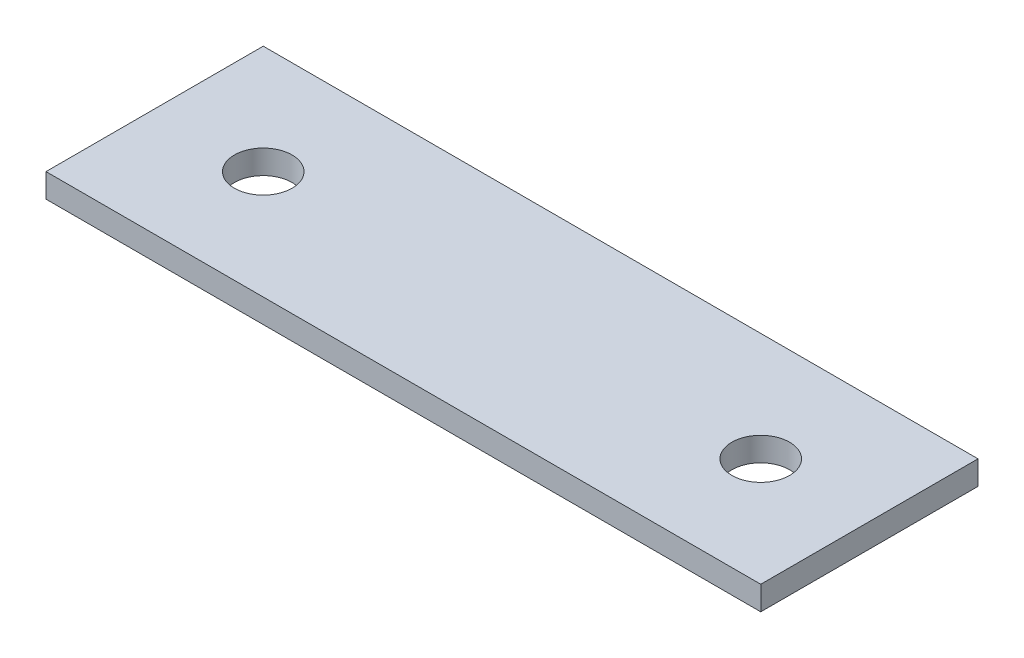
SolidWorks part; units mm, degrees
ref_plane "Front Plane" through (0, 0, 0) normal (0, 0, 1) x (1, 0, 0)
ref_plane "Top Plane" through (0, 0, 0) normal (0, 1, 0) x (1, 0, 0)
ref_plane "Right Plane" through (0, 0, 0) normal (1, 0, 0) x (0, 0, -1)
sketch "Sketch1" plane through (0, 0, 0) normal (0, 1, 0) x (1, 0, 0)
  line L0 (-41.783, 0) -> (41.783, 0) construction
  line L1 (-41.783, 12.7) -> (41.783, 12.7)
  line L2 (-41.783, 12.7) -> (-41.783, -12.7)
  line L3 (-41.783, -12.7) -> (41.783, -12.7)
  line L4 (41.783, 12.7) -> (41.783, -12.7)
  line L5 (-41.783, 12.7) -> (41.783, -12.7) construction
  line L6 (-41.783, -12.7) -> (41.783, 12.7) construction
  circle A0 centre (-29.083, 0) radius 3.3734
  circle A1 centre (29.083, 0) radius 3.3734
  point P0 (0, 0)
  dimension "D3" = 6.7469
  dimension "D4" = 6.7469
  dimension "D1" = 83.566
  dimension "D2" = 25.4
  dimension "D5" = 12.7
  dimension "D6" = 12.7
extrude "Boss-Extrude1" add sketch "Sketch1" along normal blind 2.794
